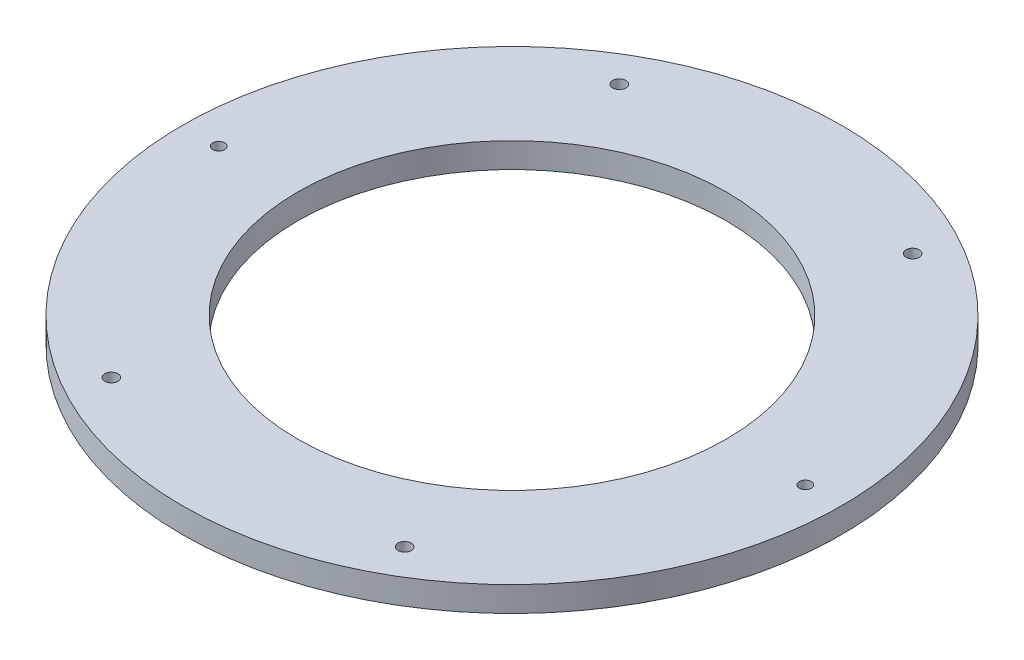
SolidWorks part; units mm, degrees
material "Pine"
ref_plane "Front Plane" through (0, 0, 0) normal (0, 0, 1) x (1, 0, 0)
ref_plane "Top Plane" through (0, 0, 0) normal (0, 1, 0) x (1, 0, 0)
ref_plane "Right Plane" through (0, 0, 0) normal (1, 0, 0) x (0, 0, -1)
sketch "Sketch1" plane through (0, 0, 0) normal (0, 1, 0) x (1, 0, 0)
  circle A0 centre (0, 0) radius 250
  circle A1 centre (0, 0) radius 162.5
  dimension "D1" = 500
  dimension "D2" = 325
extrude "Boss-Extrude1" add sketch "Sketch1" along normal mid plane 19
sketch "Sketch2" plane through (0, 9.5, 0) normal (0, 1, 0) x (1, 0, 0)
  line L0 (0, -1000) -> (0, 49000) construction
  line L1 (-1000, 0) -> (49000, 0) construction
  line L2 (-500, -866.0254) -> (24500, 42435.2448) construction
  line L3 (-498.7513, 863.8626) -> (24438.8143, -42329.268) construction
  line L4 (113.75, 197.0208) -> (122.4139, 192.0187) construction
  line L5 (125, 216.5064) -> (163.0669, 194.5284) construction
  circle A0 centre (-111.25, 192.6907) radius 5
  circle A1 centre (111.25, 192.6907) radius 5
  circle A2 centre (222.5, 0) radius 4.5
  circle A3 centre (-111.25, -192.6907) radius 5
  circle A4 centre (-222.5, 0) radius 4.5
  circle A5 centre (111.25, -192.6907) radius 5
  circle A6 centre (0, 0) radius 250 construction
  dimension "D1" = 10
  dimension "D2" = 10
  dimension "D3" = 9
  dimension "D5" = 222.5
  dimension "D6" = 222.5
  dimension "D4" = 222.5
  dimension "D7" = 30
  dimension "D8" = 30
extrude "Cut-Extrude1" cut sketch "Sketch2" against normal through all
sketch "Sketch3" plane through (0, 9.5, 0) normal (0, 1, 0) x (1, 0, 0)
  line L0 (-250, 0) -> (-227, 0) construction
  line L1 (-218, 0) -> (-195, 0) construction
  circle A0 centre (0, 0) radius 195
  circle A1 centre (0, 0) radius 250 construction
  circle A2 centre (-222.5, 0) radius 4.5 construction
  dimension "D1" = 23
